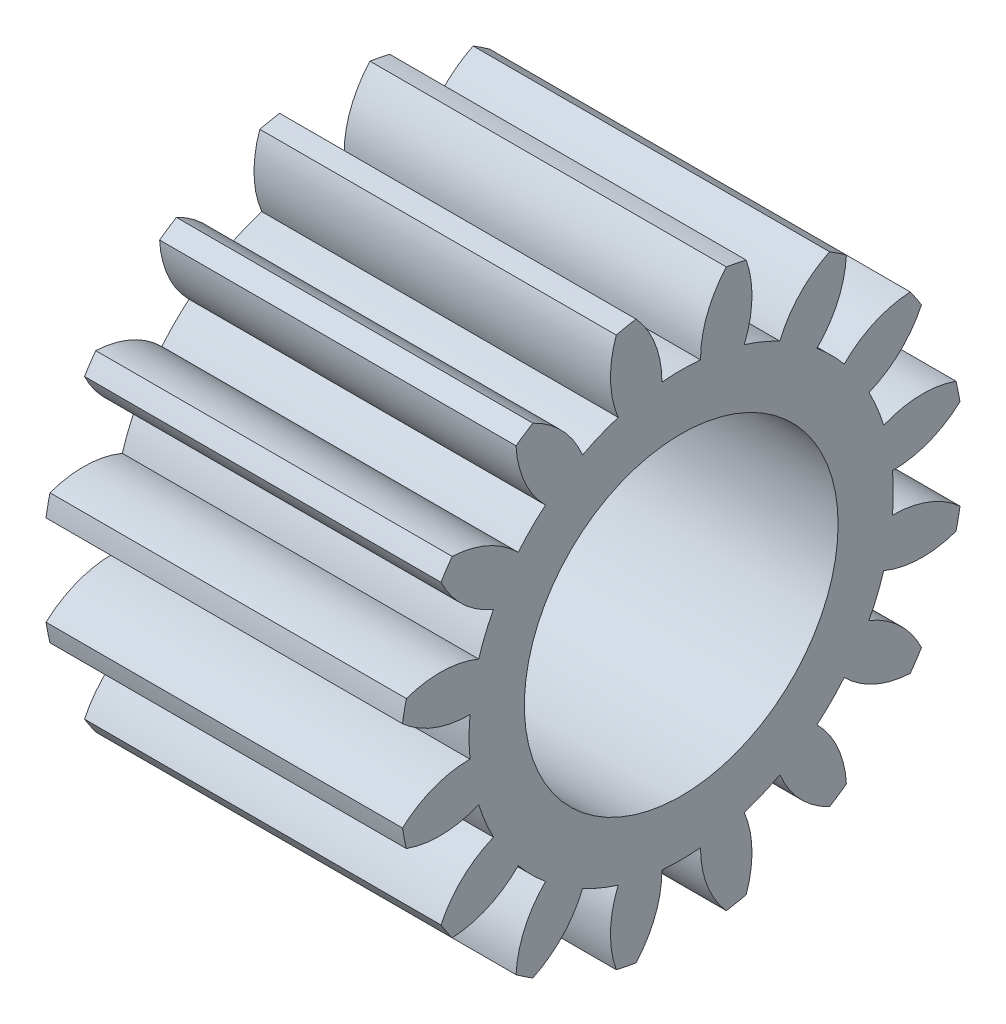
SolidWorks part; units mm, degrees
ref_plane "Front Plane" through (0, 0, 0) normal (0, 0, 1) x (1, 0, 0)
ref_plane "Top Plane" through (0, 0, 0) normal (0, 1, 0) x (1, 0, 0)
ref_plane "Right Plane" through (0, 0, 0) normal (1, 0, 0) x (0, 0, -1)
ref_plane "Plane1" through (0, 0, 0) normal (0, 0, -1) x (-1, 0, 0)
sketch "Sketch1" plane through (0, 0, 0) normal (0, 0, -1) x (-1, 0, 0)
  line L0 (-14.4272, 11.43) -> (-14.4272, 0)
  line L1 (-14.4272, 0) -> (0, 0)
  line L2 (0, 0) -> (0, 11.43)
  line L3 (0, 11.43) -> (-14.4272, 11.43)
  line L4 (-14.4272, 0) -> (0, 0) construction
revolve "Revolve1" add sketch "Sketch1" angle 360 about L4
sketch "Sketch2" plane through (14.4272, 0, 0) normal (1, 0, 0) x (0, 0, -1)
  arc A0 (9.2706, 6.6859) -> (6.6859, 9.2706) centre (0, 0) ccw
  arc A1 (6.6859, 9.2706) -> (5.4932, 6.5977) centre (2.6272, 9.479) cw
  arc A2 (5.4932, 6.5977) -> (6.5977, 5.4932) centre (0, 0) cw
  arc A3 (6.5977, 5.4932) -> (9.2706, 6.6859) centre (9.479, 2.6272) cw
extrude "Cut-Extrude1" cut sketch "Sketch2" against normal through all
sketch "Sketch3" plane through (14.4272, 0, 0) normal (1, 0, 0) x (0, 0, -1)
  arc A0 (11.1235, 2.6292) -> (9.7246, 6.0064) centre (0, 0) ccw
  arc A1 (9.7246, 6.0064) -> (7.5999, 3.9933) centre (6.0547, 7.7521) cw
  arc A2 (7.5999, 3.9933) -> (8.1977, 2.5503) centre (0, 0) cw
  arc A3 (8.1977, 2.5503) -> (11.1235, 2.6292) centre (9.7629, -1.2002) cw
extrude "Cut-Extrude2" cut sketch "Sketch3" against normal through all
sketch "Sketch4" plane through (14.4272, 0, 0) normal (1, 0, 0) x (0, 0, -1)
  arc A0 (11.2829, -1.8277) -> (11.2829, 1.8277) centre (0, 0) ccw
  arc A1 (11.2829, 1.8277) -> (8.5496, 0.781) centre (8.5604, 4.845) cw
  arc A2 (8.5496, 0.781) -> (8.5496, -0.781) centre (0, 0) cw
  arc A3 (8.5496, -0.781) -> (11.2829, -1.8277) centre (8.5604, -4.845) cw
extrude "Cut-Extrude3" cut sketch "Sketch4" against normal through all
sketch "Sketch5" plane through (14.4272, 0, 0) normal (1, 0, 0) x (0, 0, -1)
  arc A0 (9.7246, -6.0064) -> (11.1235, -2.6292) centre (0, 0) ccw
  arc A1 (11.1235, -2.6292) -> (8.1977, -2.5503) centre (9.7629, 1.2002) cw
  arc A2 (8.1977, -2.5503) -> (7.5999, -3.9933) centre (0, 0) cw
  arc A3 (7.5999, -3.9933) -> (9.7246, -6.0064) centre (6.0547, -7.7521) cw
extrude "Cut-Extrude4" cut sketch "Sketch5" against normal through all
sketch "Sketch6" plane through (14.4272, 0, 0) normal (1, 0, 0) x (0, 0, -1)
  arc A0 (6.6859, -9.2706) -> (9.2706, -6.6859) centre (0, 0) ccw
  arc A1 (9.2706, -6.6859) -> (6.5977, -5.4932) centre (9.479, -2.6272) cw
  arc A2 (6.5977, -5.4932) -> (5.4932, -6.5977) centre (0, 0) cw
  arc A3 (5.4932, -6.5977) -> (6.6859, -9.2706) centre (2.6272, -9.479) cw
extrude "Cut-Extrude5" cut sketch "Sketch6" against normal through all
sketch "Sketch7" plane through (14.4272, 0, 0) normal (1, 0, 0) x (0, 0, -1)
  arc A0 (2.6292, -11.1235) -> (6.0064, -9.7246) centre (0, 0) ccw
  arc A1 (6.0064, -9.7246) -> (3.9933, -7.5999) centre (7.7521, -6.0547) cw
  arc A2 (3.9933, -7.5999) -> (2.5503, -8.1977) centre (0, 0) cw
  arc A3 (2.5503, -8.1977) -> (2.6292, -11.1235) centre (-1.2002, -9.7629) cw
extrude "Cut-Extrude6" cut sketch "Sketch7" against normal through all
sketch "Sketch8" plane through (14.4272, 0, 0) normal (1, 0, 0) x (0, 0, -1)
  arc A0 (-1.8277, -11.2829) -> (1.8277, -11.2829) centre (0, 0) ccw
  arc A1 (1.8277, -11.2829) -> (0.781, -8.5496) centre (4.845, -8.5604) cw
  arc A2 (0.781, -8.5496) -> (-0.781, -8.5496) centre (0, 0) cw
  arc A3 (-0.781, -8.5496) -> (-1.8277, -11.2829) centre (-4.845, -8.5604) cw
extrude "Cut-Extrude7" cut sketch "Sketch8" against normal through all
sketch "Sketch9" plane through (14.4272, 0, 0) normal (1, 0, 0) x (0, 0, -1)
  arc A0 (-6.0064, -9.7246) -> (-2.6292, -11.1235) centre (0, 0) ccw
  arc A1 (-2.6292, -11.1235) -> (-2.5503, -8.1977) centre (1.2002, -9.7629) cw
  arc A2 (-2.5503, -8.1977) -> (-3.9933, -7.5999) centre (0, 0) cw
  arc A3 (-3.9933, -7.5999) -> (-6.0064, -9.7246) centre (-7.7521, -6.0547) cw
extrude "Cut-Extrude8" cut sketch "Sketch9" against normal through all
sketch "Sketch10" plane through (14.4272, 0, 0) normal (1, 0, 0) x (0, 0, -1)
  arc A0 (-9.2706, -6.6859) -> (-6.6859, -9.2706) centre (0, 0) ccw
  arc A1 (-6.6859, -9.2706) -> (-5.4932, -6.5977) centre (-2.6272, -9.479) cw
  arc A2 (-5.4932, -6.5977) -> (-6.5977, -5.4932) centre (0, 0) cw
  arc A3 (-6.5977, -5.4932) -> (-9.2706, -6.6859) centre (-9.479, -2.6272) cw
extrude "Cut-Extrude9" cut sketch "Sketch10" against normal through all
sketch "Sketch11" plane through (14.4272, 0, 0) normal (1, 0, 0) x (0, 0, -1)
  arc A0 (-11.1235, -2.6292) -> (-9.7246, -6.0064) centre (0, 0) ccw
  arc A1 (-9.7246, -6.0064) -> (-7.5999, -3.9933) centre (-6.0547, -7.7521) cw
  arc A2 (-7.5999, -3.9933) -> (-8.1977, -2.5503) centre (0, 0) cw
  arc A3 (-8.1977, -2.5503) -> (-11.1235, -2.6292) centre (-9.7629, 1.2002) cw
extrude "Cut-Extrude10" cut sketch "Sketch11" against normal through all
sketch "Sketch12" plane through (14.4272, 0, 0) normal (1, 0, 0) x (0, 0, -1)
  arc A0 (-11.2829, 1.8277) -> (-11.2829, -1.8277) centre (0, 0) ccw
  arc A1 (-11.2829, -1.8277) -> (-8.5496, -0.781) centre (-8.5604, -4.845) cw
  arc A2 (-8.5496, -0.781) -> (-8.5496, 0.781) centre (0, 0) cw
  arc A3 (-8.5496, 0.781) -> (-11.2829, 1.8277) centre (-8.5604, 4.845) cw
extrude "Cut-Extrude11" cut sketch "Sketch12" against normal through all
sketch "Sketch13" plane through (14.4272, 0, 0) normal (1, 0, 0) x (0, 0, -1)
  arc A0 (-9.7246, 6.0064) -> (-11.1235, 2.6292) centre (0, 0) ccw
  arc A1 (-11.1235, 2.6292) -> (-8.1977, 2.5503) centre (-9.7629, -1.2002) cw
  arc A2 (-8.1977, 2.5503) -> (-7.5999, 3.9933) centre (0, 0) cw
  arc A3 (-7.5999, 3.9933) -> (-9.7246, 6.0064) centre (-6.0547, 7.7521) cw
extrude "Cut-Extrude12" cut sketch "Sketch13" against normal through all
sketch "Sketch14" plane through (14.4272, 0, 0) normal (1, 0, 0) x (0, 0, -1)
  arc A0 (-6.6859, 9.2706) -> (-9.2706, 6.6859) centre (0, 0) ccw
  arc A1 (-9.2706, 6.6859) -> (-6.5977, 5.4932) centre (-9.479, 2.6272) cw
  arc A2 (-6.5977, 5.4932) -> (-5.4932, 6.5977) centre (0, 0) cw
  arc A3 (-5.4932, 6.5977) -> (-6.6859, 9.2706) centre (-2.6272, 9.479) cw
extrude "Cut-Extrude13" cut sketch "Sketch14" against normal through all
sketch "Sketch15" plane through (14.4272, 0, 0) normal (1, 0, 0) x (0, 0, -1)
  arc A0 (-2.6292, 11.1235) -> (-6.0064, 9.7246) centre (0, 0) ccw
  arc A1 (-6.0064, 9.7246) -> (-3.9933, 7.5999) centre (-7.7521, 6.0547) cw
  arc A2 (-3.9933, 7.5999) -> (-2.5503, 8.1977) centre (0, 0) cw
  arc A3 (-2.5503, 8.1977) -> (-2.6292, 11.1235) centre (1.2002, 9.7629) cw
extrude "Cut-Extrude14" cut sketch "Sketch15" against normal through all
sketch "Sketch16" plane through (14.4272, 0, 0) normal (1, 0, 0) x (0, 0, -1)
  arc A0 (1.8277, 11.2829) -> (-1.8277, 11.2829) centre (0, 0) ccw
  arc A1 (-1.8277, 11.2829) -> (-0.781, 8.5496) centre (-4.845, 8.5604) cw
  arc A2 (-0.781, 8.5496) -> (0.781, 8.5496) centre (0, 0) cw
  arc A3 (0.781, 8.5496) -> (1.8277, 11.2829) centre (4.845, 8.5604) cw
extrude "Cut-Extrude15" cut sketch "Sketch16" against normal through all
sketch "Sketch17" plane through (14.4272, 0, 0) normal (1, 0, 0) x (0, 0, -1)
  arc A0 (6.0064, 9.7246) -> (2.6292, 11.1235) centre (0, 0) ccw
  arc A1 (2.6292, 11.1235) -> (2.5503, 8.1977) centre (-1.2002, 9.7629) cw
  arc A2 (2.5503, 8.1977) -> (3.9933, 7.5999) centre (0, 0) cw
  arc A3 (3.9933, 7.5999) -> (6.0064, 9.7246) centre (7.7521, 6.0547) cw
extrude "Cut-Extrude16" cut sketch "Sketch17" against normal through all
hole_wizard "1/4 (0.25) Diameter Hole1" positions "Sketch19" profile "Sketch18" hole size "1/4" standard "ANSI Inch"
sketch "Sketch19" plane through (14.4272, 0, 0) normal (1, 0, 0) x (0, 0, -1)
  point P0 (0, 0)
sketch "Sketch18" plane through (14.4272, 0, 0) normal (0, 1, 0) x (0, 0, -1)
  line L0 (0, 0) -> (0, 14.4272)
  line L1 (0, 14.4272) -> (6.35, 14.4272)
  line L2 (6.35, 14.4272) -> (6.35, 0)
  line L5 (6.35, 0) -> (0, 0)
  line L11 (0, -6.35) -> (0, 107.95) construction
  dimension "Thru Hole Dia." = 12.7
  dimension "Thru Hole Depth" = 14.4272
sketch "Sketch20" plane through (14.4272, 0, 0) normal (1, 0, 0) x (0, 0, -1)
  circle A0 centre (0, 0) radius 6.985
